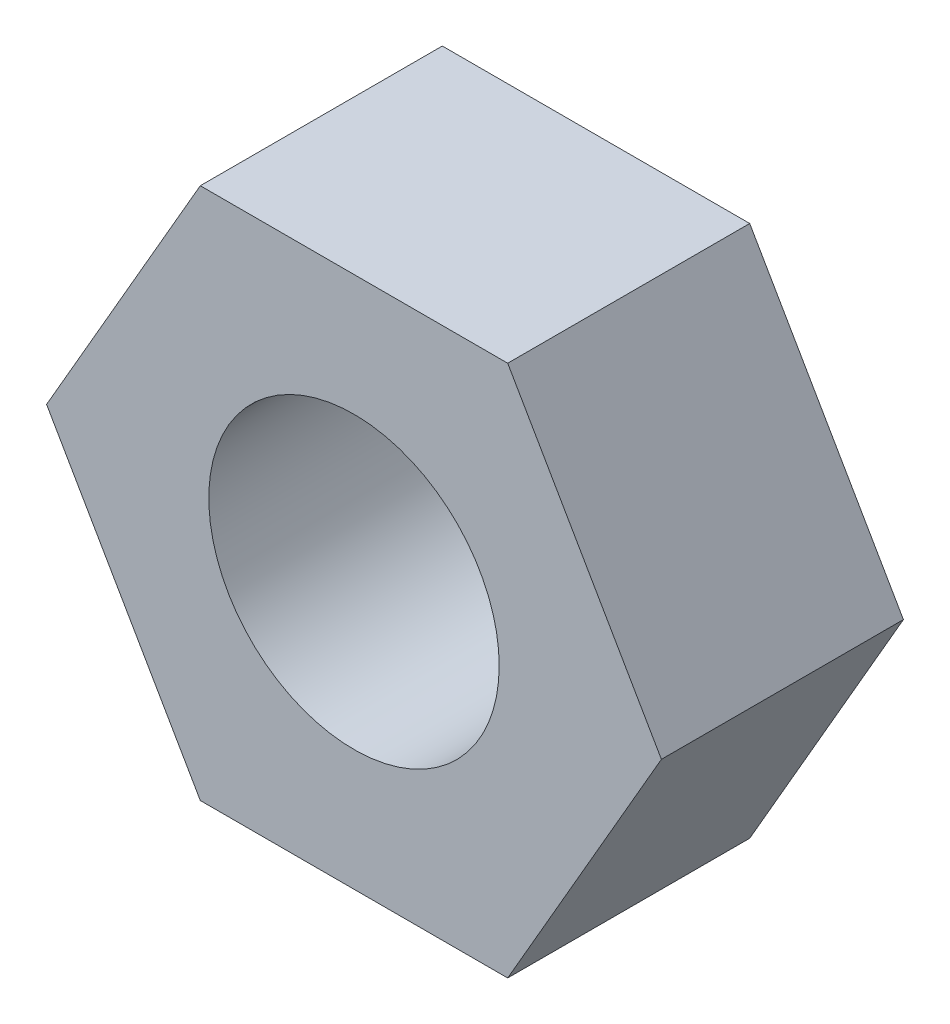
SolidWorks part; units mm, degrees
ref_plane "Front" through (0, 0, 0) normal (0, 0, 1) x (1, 0, 0)
ref_plane "Top" through (0, 0, 0) normal (0, 1, 0) x (1, 0, 0)
ref_plane "Right" through (0, 0, 0) normal (1, 0, 0) x (0, 0, -1)
sketch "Эскиз1" plane through (0, 0, 0) normal (0, 0, 1) x (1, 0, 0)
  line L1 (1.5877, -2.75) -> (3.1754, 0)
  line L2 (3.1754, 0) -> (1.5877, 2.75)
  line L3 (1.5877, 2.75) -> (-1.5877, 2.75)
  line L4 (-1.5877, 2.75) -> (-3.1754, 0)
  line L5 (-3.1754, 0) -> (-1.5877, -2.75)
  line L6 (-1.5877, -2.75) -> (1.5877, -2.75)
  circle A0 centre (0, 0) radius 2.75 construction
  circle A1 centre (0, 0) radius 1.5
  dimension "D1" = 3
  dimension "D2" = 5.5
extrude "Бобышка-Вытянуть1" add sketch "Эскиз1" along normal blind 2.5
